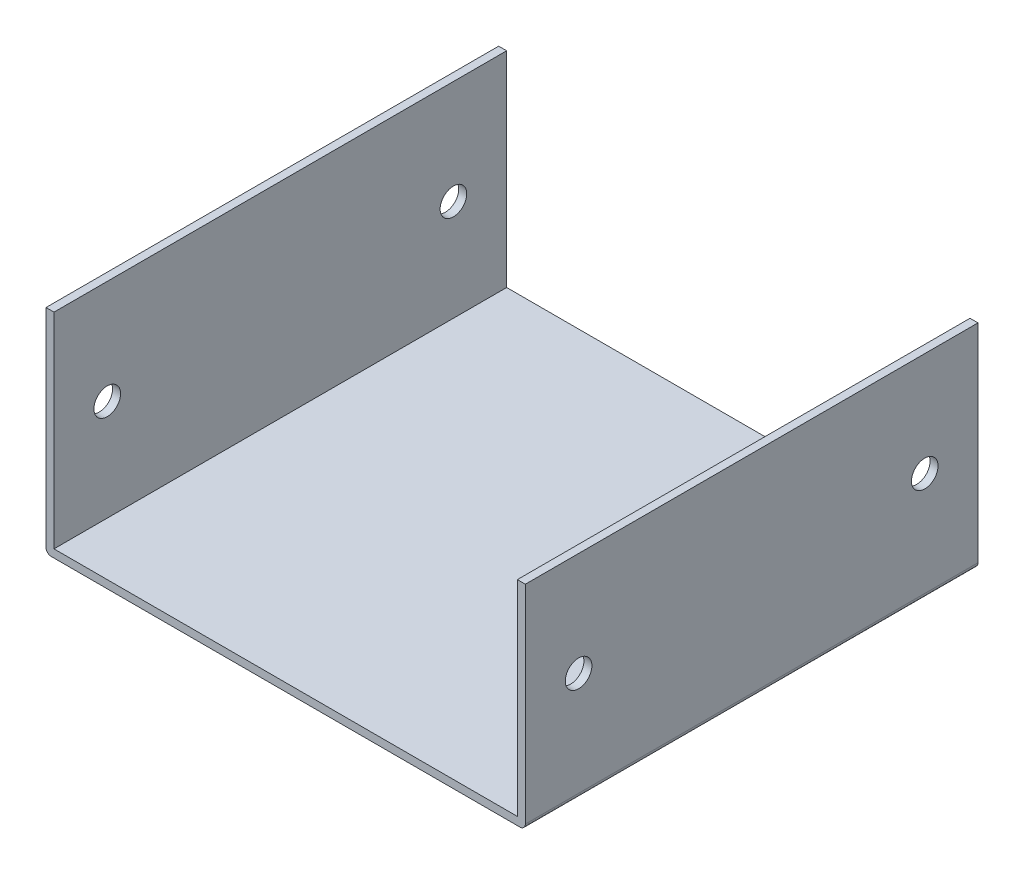
SolidWorks part; units mm, degrees
ref_plane "Front Plane" through (0, 0, 0) normal (0, 0, 1) x (1, 0, 0)
ref_plane "Top Plane" through (0, 0, 0) normal (0, 1, 0) x (1, 0, 0)
ref_plane "Right Plane" through (0, 0, 0) normal (1, 0, 0) x (0, 0, -1)
sketch "Sketch1" plane through (0, 0, 0) normal (0, 0, 1) x (1, 0, 0)
  line L0 (-43.5432, 35.7342) -> (-43.5432, -41.2658)
  line L1 (-43.5432, -41.2658) -> (130.4568, -41.2658)
  line L2 (130.4568, -41.2658) -> (130.4568, 35.7342)
  line L3 (-46.5432, 35.7342) -> (-46.5432, -44.2658)
  line L4 (-46.5432, -44.2658) -> (133.4568, -44.2658)
  line L5 (133.4568, -44.2658) -> (133.4568, 35.7342)
  line L6 (-46.8258, 35.7342) -> (-43.5432, 35.7342)
  line L7 (130.4568, 35.7342) -> (133.4568, 35.7342)
  dimension "D2" = 180
  dimension "D3" = 80
  dimension "D4" = 80
  dimension "D1" = 3
extrude "Boss-Extrude1" add sketch "Sketch1" along normal blind 170 contours L7 L2 L1 L0 L6 L3 L4 L5
fillet "Fillet1" radius 2 1 edges at (-46.5432, -44.2658, 85)
fillet "Fillet2" radius 2 1 edges at (133.4568, -44.2658, 85)
sketch "Sketch2" plane through (133.4568, 0, 0) normal (1, 0, 0) x (0, 0, -1)
  line L0 (-170, -42.2658) -> (-170, 35.7342) construction
  line L1 (0, -42.2658) -> (0, 35.7342) construction
  circle A0 centre (-150, -3.2658) radius 5
  circle A1 centre (-20, -3.2658) radius 5
  dimension "D1" = 10
  dimension "D2" = 10
  dimension "D3" = 20
  dimension "D4" = 20
extrude "Cut-Extrude2" cut sketch "Sketch2" against normal blind 455
